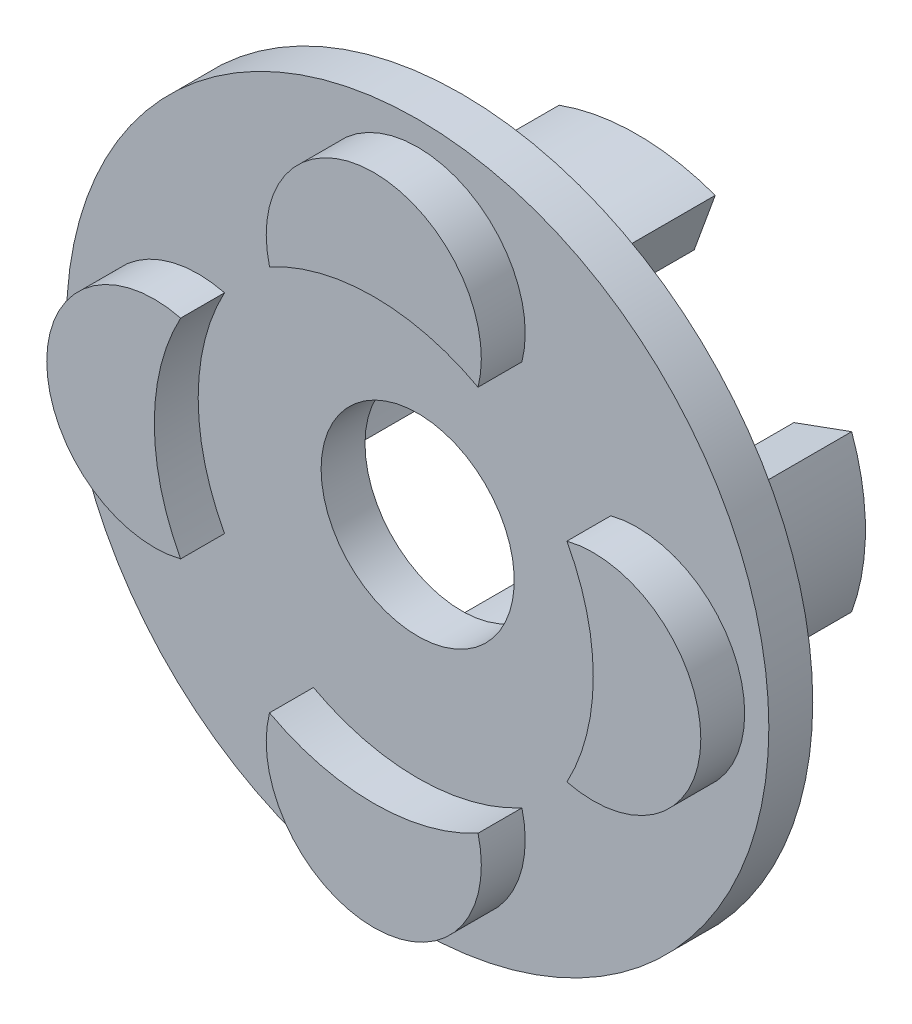
SolidWorks part; units mm, degrees
ref_plane "前视基准面" through (0, 0, 0) normal (0, 0, 1) x (1, 0, 0)
ref_plane "上视基准面" through (0, 0, 0) normal (0, 1, 0) x (1, 0, 0)
ref_plane "右视基准面" through (0, 0, 0) normal (1, 0, 0) x (0, 0, -1)
sketch "草图1" plane through (0, 0, 0) normal (0, 0, 1) x (1, 0, 0)
  circle A0 centre (0, 0) radius 40
  dimension "D1" = 80
extrude "凸台-拉伸1" add sketch "草图1" along normal blind 5
sketch "草图2" plane through (0, 0, 0) normal (0, 0, -1) x (-1, 0, 0)
  line L0 (-6.4984, 17.8542) -> (-8.8925, 24.432)
  line L1 (0, 19) -> (0, 26) construction
  line L2 (6.4984, 17.8542) -> (8.8925, 24.432)
  line L3 (0, 0) -> (-6.4984, 17.8542) construction
  line L4 (0, 0) -> (0, 19) construction
  line L5 (0, 0) -> (6.4984, 17.8542) construction
  line L6 (17.8542, 6.4984) -> (24.432, 8.8925)
  line L7 (17.8542, -6.4984) -> (24.432, -8.8925)
  line L8 (6.4984, -17.8542) -> (8.8925, -24.432)
  line L9 (-6.4984, -17.8542) -> (-8.8925, -24.432)
  line L10 (-17.8542, -6.4984) -> (-24.432, -8.8925)
  line L11 (-17.8542, 6.4984) -> (-24.432, 8.8925)
  arc A0 (8.8925, 24.432) -> (-8.8925, 24.432) centre (0, 0) ccw
  arc A1 (6.4984, 17.8542) -> (-6.4984, 17.8542) centre (0, 0) ccw
  arc A2 (-8.8925, 24.432) -> (8.8925, 24.432) centre (0, 0) ccw construction
  arc A3 (-6.4984, 17.8542) -> (6.4984, 17.8542) centre (0, 0) ccw construction
  arc A4 (24.432, -8.8925) -> (24.432, 8.8925) centre (0, 0) ccw
  arc A5 (17.8542, -6.4984) -> (17.8542, 6.4984) centre (0, 0) ccw
  arc A6 (-8.8925, -24.432) -> (8.8925, -24.432) centre (0, 0) ccw
  arc A7 (-6.4984, -17.8542) -> (6.4984, -17.8542) centre (0, 0) ccw
  arc A8 (-24.432, 8.8925) -> (-24.432, -8.8925) centre (0, 0) ccw
  arc A9 (-17.8542, 6.4984) -> (-17.8542, -6.4984) centre (0, 0) ccw
  point P23 (0, 0)
  dimension "D1" = 52
  dimension "D2" = 38
  dimension "D4" = 40
  dimension "D3" = 4
extrude "凸台-拉伸2" add sketch "草图2" along normal blind 20
sketch "草图3" plane through (0, 0, 0) normal (0, 0, -1) x (-1, 0, 0)
  circle A0 centre (0, 0) radius 11
  dimension "D1" = 22
extrude "切除-拉伸1" cut sketch "草图3" against normal blind 5
sketch "草图5" plane through (0, 0, 5) normal (0, 0, 1) x (1, 0, 0)
  arc A0 (-21.9988, -11.8767) -> (-11.8767, -21.9987) centre (0, 0) ccw construction
  arc A1 (11.8767, 21.9988) -> (-11.8767, 21.9988) centre (0, 25) ccw
  arc A2 (21.9988, 11.8767) -> (21.9987, -11.8767) centre (25, 0) ccw construction
  arc A3 (-11.8767, -21.9987) -> (11.8767, -21.9988) centre (0, -25) ccw construction
  arc A4 (-21.9988, -11.8767) -> (-21.9987, 11.8767) centre (-25, 0) ccw construction
  arc A5 (-11.8767, 21.9988) -> (11.8767, 21.9988) centre (0, 0) cw
  arc A6 (-11.8767, 21.9988) -> (11.8767, 21.9988) centre (0, 25) ccw construction
  arc A7 (-21.9987, 11.8767) -> (-21.9988, -11.8767) centre (-25, 0) ccw construction
  arc A8 (-21.9987, 11.8767) -> (-21.9988, -11.8767) centre (0, 0) ccw construction
  arc A9 (11.8767, -21.9988) -> (-11.8767, -21.9987) centre (0, -25) ccw construction
  arc A10 (-11.8767, -21.9987) -> (11.8767, -21.9988) centre (0, 0) ccw construction
  arc A11 (11.8767, -21.9988) -> (21.9987, -11.8767) centre (0, 0) ccw construction
  arc A12 (21.9987, -11.8767) -> (21.9988, 11.8767) centre (25, 0) ccw construction
  arc A13 (21.9987, -11.8767) -> (21.9988, 11.8767) centre (0, 0) ccw construction
  arc A14 (21.9988, 11.8767) -> (-21.9987, 11.8767) centre (0, 0) ccw construction
  arc A15 (21.9987, -11.8767) -> (21.9988, 11.8767) centre (25, 0) ccw
  arc A16 (21.9988, 11.8767) -> (21.9987, -11.8767) centre (0, 0) cw
  arc A17 (-11.8767, -21.9987) -> (11.8767, -21.9988) centre (0, -25) ccw
  arc A18 (11.8767, -21.9988) -> (-11.8767, -21.9987) centre (0, 0) cw
  arc A19 (-21.9987, 11.8767) -> (-21.9988, -11.8767) centre (-25, 0) ccw
  arc A20 (-21.9988, -11.8767) -> (-21.9987, 11.8767) centre (0, 0) cw
  point P14 (0, 0)
  point P27 (0, 0)
  dimension "D1" = 24.5
  dimension "D2" = 50
  dimension "D3" = 4
extrude "凸台-拉伸5" add sketch "草图5" along normal blind 5
